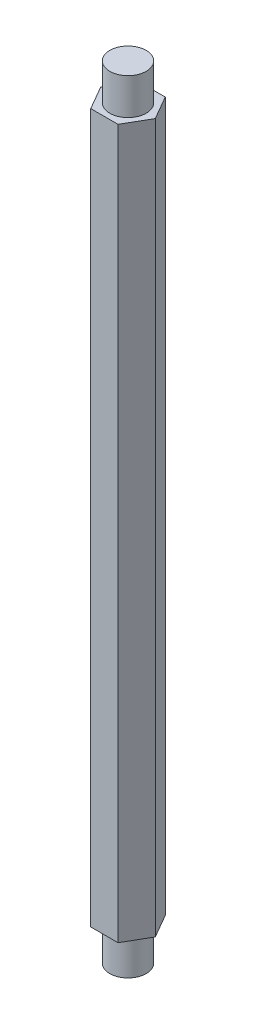
SolidWorks part; units mm, degrees
ref_plane "前视基准面" through (0, 0, 0) normal (0, 0, 1) x (1, 0, 0)
ref_plane "上视基准面" through (0, 0, 0) normal (0, 1, 0) x (1, 0, 0)
ref_plane "右视基准面" through (0, 0, 0) normal (1, 0, 0) x (0, 0, -1)
sketch "草图1" plane through (0, 0, 0) normal (0, 1, 0) x (1, 0, 0)
  circle A0 centre (0, 0) radius 1
  dimension "D1" = 2
extrude "凸台-拉伸1" add sketch "草图1" along normal blind 2
sketch "草图2" plane through (0, 2, 0) normal (0, 1, 0) x (1, 0, 0)
  line L1 (1.5011, 0) -> (0.7506, 1.3)
  line L2 (0.7506, 1.3) -> (-0.7506, 1.3)
  line L3 (-0.7506, 1.3) -> (-1.5011, 0)
  line L4 (-1.5011, 0) -> (-0.7506, -1.3)
  line L5 (-0.7506, -1.3) -> (0.7506, -1.3)
  line L6 (0.7506, -1.3) -> (1.5011, 0)
  circle A0 centre (0, 0) radius 1.3 construction
  dimension "D1" = 2.6
extrude "凸台-拉伸2" add sketch "草图2" along normal blind 39
sketch "草图3" plane through (0, 41, 0) normal (0, 1, 0) x (1, 0, 0)
  circle A0 centre (0, 0) radius 1
  dimension "D1" = 2
extrude "凸台-拉伸3" add sketch "草图3" along normal blind 2
